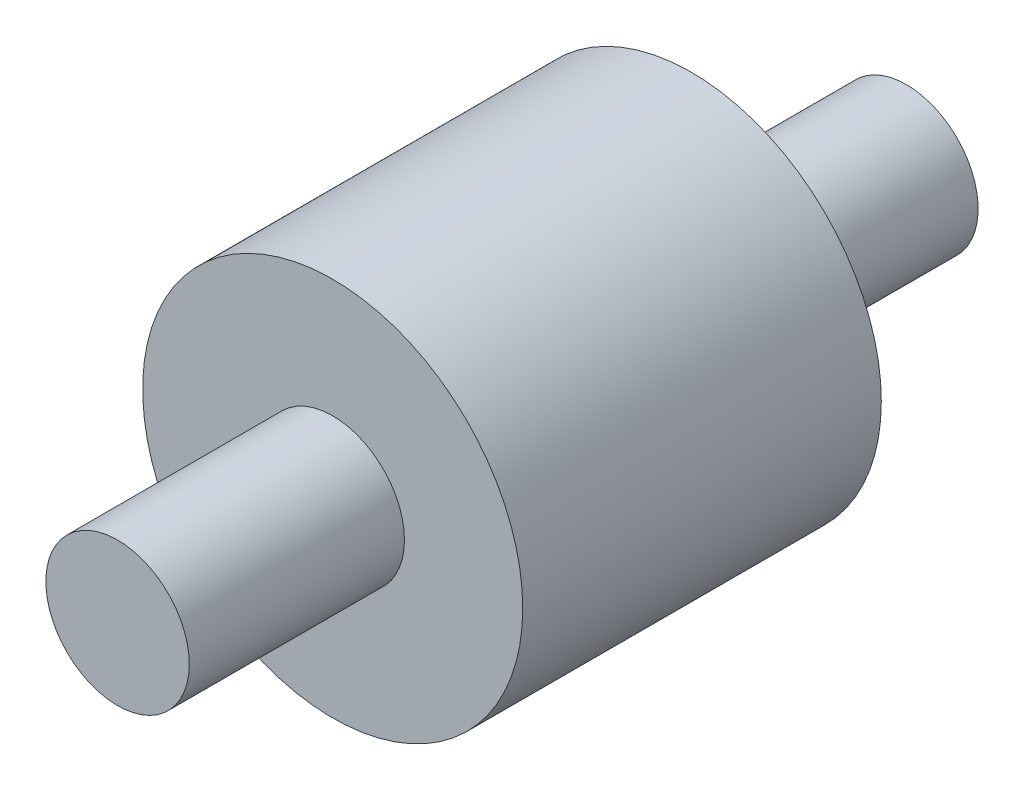
SolidWorks part; units mm, degrees
ref_plane "Front Plane" through (0, 0, 0) normal (0, 0, 1) x (1, 0, 0)
ref_plane "Top Plane" through (0, 0, 0) normal (0, 1, 0) x (1, 0, 0)
ref_plane "Right Plane" through (0, 0, 0) normal (1, 0, 0) x (0, 0, -1)
sketch "Sketch1" plane through (0, 0, 0) normal (0, 0, 1) x (1, 0, 0)
  circle A0 centre (0, 0) radius 26.5
  dimension "D1" = 53
extrude "Boss-Extrude1" add sketch "Sketch1" along normal mid plane 50
sketch "Sketch2" plane through (0, 0, -25) normal (0, 0, -1) x (-1, 0, 0)
  circle A0 centre (0, 0) radius 10
  dimension "D1" = 20
extrude "Boss-Extrude2" add sketch "Sketch2" along normal blind 30
sketch "Sketch3" plane through (0, 0, 25) normal (0, 0, 1) x (1, 0, 0)
  circle A0 centre (0, 0) radius 10
  dimension "D1" = 20
extrude "Boss-Extrude3" add sketch "Sketch3" along normal blind 30
